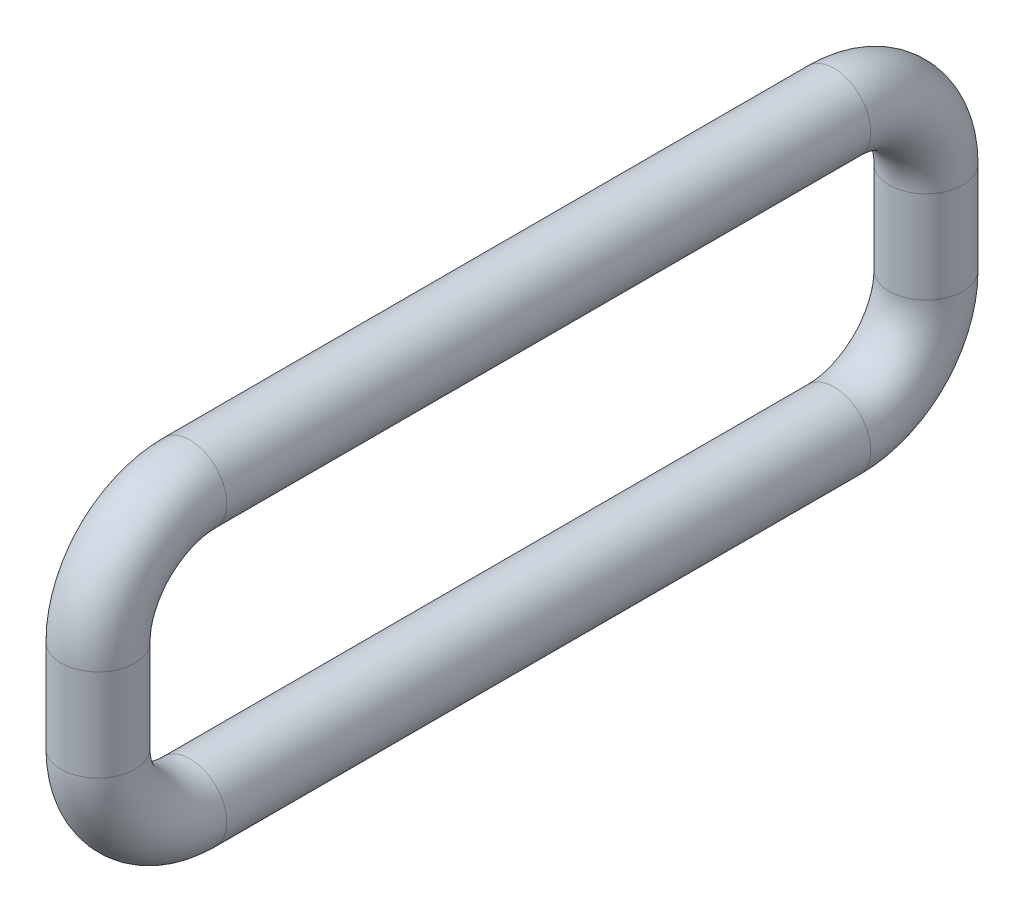
SolidWorks part; units mm, degrees
material "СТ3КП"
ref_plane "Спереди" through (0, 0, 0) normal (0, 0, 1) x (1, 0, 0)
ref_plane "Сверху" through (0, 0, 0) normal (0, 1, 0) x (1, 0, 0)
ref_plane "Справа" through (0, 0, 0) normal (1, 0, 0) x (0, 0, -1)
sketch "Эскиз1" plane through (0, 0, 0) normal (1, 0, 0) x (0, 0, -1)
  line L0 (-15, 15) -> (-15, -15) construction
  line L3 (0, -15) -> (35, -15)
  line L4 (45, 5) -> (45, -5)
  line L5 (-15, -15) -> (15, 15) construction
  line L6 (15, 15) -> (15, -15) construction
  line L7 (0, -1000) -> (0, 49000) construction
  line L8 (0, 15) -> (35, 15)
  arc A0 (35, 15) -> (45, 5) centre (35, 5) cw
  arc A1 (35, -15) -> (45, -5) centre (35, -5) ccw
  point P4 (45, 0)
  point P9 (0, 0)
  point P12 (15, 0)
  dimension "D4" = 10
  dimension "D1" = 30
  dimension "D2" = 30
  dimension "D3" = 30
sketch "Эскиз2" plane through (0, 0, 0) normal (0, 0, 1) x (1, 0, 0)
  line L0 (0, -15) -> (0, -5) construction
  line L1 (0, -201000) -> (0, 249000) construction
  circle A0 centre (0, -15) radius 4
  dimension "D1" = 8
sweep "По траектории1" add profiles "Эскиз2" path "Эскиз1"
mirror "Зеркальное отражение1" of bodies 103
equation "\"D3@Эскиз1\"=\"D1@Эскиз1\""
